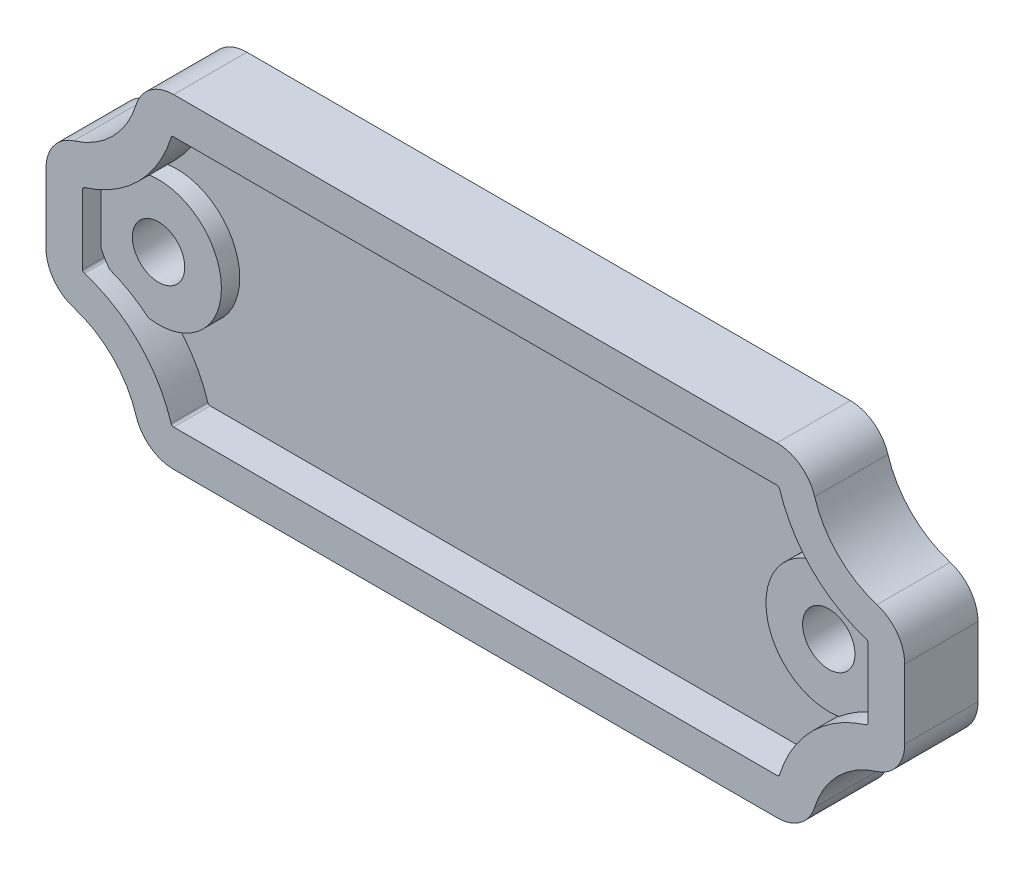
SolidWorks part; units mm, degrees
material "Brass"
ref_plane "Front Plane" through (0, 0, 0) normal (0, 0, 1) x (1, 0, 0)
ref_plane "Top Plane" through (0, 0, 0) normal (0, 1, 0) x (1, 0, 0)
ref_plane "Right Plane" through (0, 0, 0) normal (1, 0, 0) x (0, 0, -1)
sketch "Sketch1" plane through (0, 0, 0) normal (0, 0, 1) x (1, 0, 0)
  line L0 (-41, 0) -> (41, 0) construction
  line L1 (-41, -15.5) -> (41, -15.5)
  line L2 (-41, -15.5) -> (-41, 15.5)
  line L3 (-41, 15.5) -> (41, 15.5)
  line L4 (41, -15.5) -> (41, 15.5)
  line L5 (-41, -15.5) -> (41, 15.5) construction
  line L6 (-41, 15.5) -> (41, -15.5) construction
  circle A0 centre (-41, -15.5) radius 9
  circle A1 centre (-41, 15.5) radius 9
  circle A2 centre (41, 15.5) radius 9
  circle A3 centre (41, -15.5) radius 9
  circle A4 centre (-32, 0) radius 2.5
  circle A5 centre (32, 0) radius 2.5
  point P0 (0, 0)
  dimension "D1" = 18
  dimension "D2" = 18
  dimension "D3" = 18
  dimension "D4" = 18
  dimension "D7" = 5
  dimension "D9" = 5
  dimension "D5" = 31
  dimension "D6" = 82
  dimension "D8" = 9
  dimension "D10" = 9
extrude "Boss-Extrude1" add sketch "Sketch1" along normal blind 7 contours A3 L4 A2 L3 A1 L2 A0 L1 A5 A4
fillet "Fillet1" radius 3.75 8 edges at (-32, -15.5, 3.5) (-41, -6.5, 3.5) (-41, 6.5, 3.5) (-32, 15.5, 3.5) (32, -15.5, 3.5) (41, -6.5, 3.5) (41, 6.5, 3.5) (32, 15.5, 3.5)
sketch "Sketch3" plane through (0, 0, 7) normal (0, 0, 1) x (1, 0, 0)
  line L8 (-28.8139, -12) -> (28.8139, -12)
  line L9 (37.5, -3.3139) -> (37.5, 3.3139)
  line L10 (28.8139, 12) -> (-28.8139, 12)
  line L11 (-37.5, 3.3139) -> (-37.5, -3.3139)
  line L12 (-28.8139, -12) -> (28.8139, -12)
  line L13 (37.5, -3.3139) -> (37.5, 3.3139)
  line L14 (28.8139, 12) -> (-28.8139, 12)
  line L15 (-37.5, 3.3139) -> (-37.5, -3.3139)
  arc A24 (-29.0529, -11.8235) -> (-37.3235, -3.5529) centre (-41, -15.5) ccw
  arc A25 (-29.0529, -11.8235) -> (-28.8139, -12) centre (-28.8139, -11.75) ccw
  arc A26 (28.8139, -12) -> (29.0529, -11.8235) centre (28.8139, -11.75) ccw
  arc A27 (37.3235, -3.5529) -> (29.0529, -11.8235) centre (41, -15.5) ccw
  arc A28 (37.3235, -3.5529) -> (37.5, -3.3139) centre (37.25, -3.3139) ccw
  arc A29 (37.5, 3.3139) -> (37.3235, 3.5529) centre (37.25, 3.3139) ccw
  arc A30 (29.0529, 11.8235) -> (37.3235, 3.5529) centre (41, 15.5) ccw
  arc A31 (29.0529, 11.8235) -> (28.8139, 12) centre (28.8139, 11.75) ccw
  arc A32 (-28.8139, 12) -> (-29.0529, 11.8235) centre (-28.8139, 11.75) ccw
  arc A33 (-37.3235, 3.5529) -> (-29.0529, 11.8235) centre (-41, 15.5) ccw
  arc A34 (-37.3235, 3.5529) -> (-37.5, 3.3139) centre (-37.25, 3.3139) ccw
  arc A35 (-37.5, -3.3139) -> (-37.3235, -3.5529) centre (-37.25, -3.3139) ccw
  arc A36 (-29.0529, -11.8235) -> (-37.3235, -3.5529) centre (-41, -15.5) ccw
  arc A37 (-29.0529, -11.8235) -> (-28.8139, -12) centre (-28.8139, -11.75) ccw
  arc A38 (28.8139, -12) -> (29.0529, -11.8235) centre (28.8139, -11.75) ccw
  arc A39 (37.3235, -3.5529) -> (29.0529, -11.8235) centre (41, -15.5) ccw
  arc A40 (37.3235, -3.5529) -> (37.5, -3.3139) centre (37.25, -3.3139) ccw
  arc A41 (37.5, 3.3139) -> (37.3235, 3.5529) centre (37.25, 3.3139) ccw
  arc A42 (29.0529, 11.8235) -> (37.3235, 3.5529) centre (41, 15.5) ccw
  arc A43 (29.0529, 11.8235) -> (28.8139, 12) centre (28.8139, 11.75) ccw
  arc A44 (-28.8139, 12) -> (-29.0529, 11.8235) centre (-28.8139, 11.75) ccw
  arc A45 (-37.3235, 3.5529) -> (-29.0529, 11.8235) centre (-41, 15.5) ccw
  arc A46 (-37.3235, 3.5529) -> (-37.5, 3.3139) centre (-37.25, 3.3139) ccw
  arc A47 (-37.5, -3.3139) -> (-37.3235, -3.5529) centre (-37.25, -3.3139) ccw
  dimension "D1" = 3.5
extrude "Cut-Extrude1" cut sketch "Sketch3" against normal blind 3.5
sketch "Sketch4" plane through (0, 0, 3.5) normal (0, 0, 1) x (1, 0, 0)
  line L0 (0, 12) -> (0, -12) construction
  line L1 (28.8139, 12) -> (-28.8139, 12) construction
  line L2 (-28.8139, -12) -> (28.8139, -12) construction
  circle A0 centre (-32, 0) radius 2.5
  circle A1 centre (-32, 0) radius 6
  circle A2 centre (32, 0) radius 2.5
  circle A3 centre (32, 0) radius 6
  dimension "D1" = 5
  dimension "D2" = 12
extrude "Boss-Extrude2" add sketch "Sketch4" against normal offset from surface (7 mm away) 1.75 from offset 1.75
equation "\"A\"= 3.5"
equation "\"B\"= 82"
equation "\"D6@Sketch1\"=\"B\""
equation "\"D1@Boss-Extrude1\"=\"A\"*2"
equation "\"D1@Sketch3\"=\"A\""
equation "\"D1@Cut-Extrude1\"=\"A\""
equation "\"D2@Sketch4\"=5+(\"A\"*2)"
equation "\"D1@Boss-Extrude2\"=\"A\"*0.5"
equation "\"D19@Boss-Extrude2\"=\"A\"*0.5"
